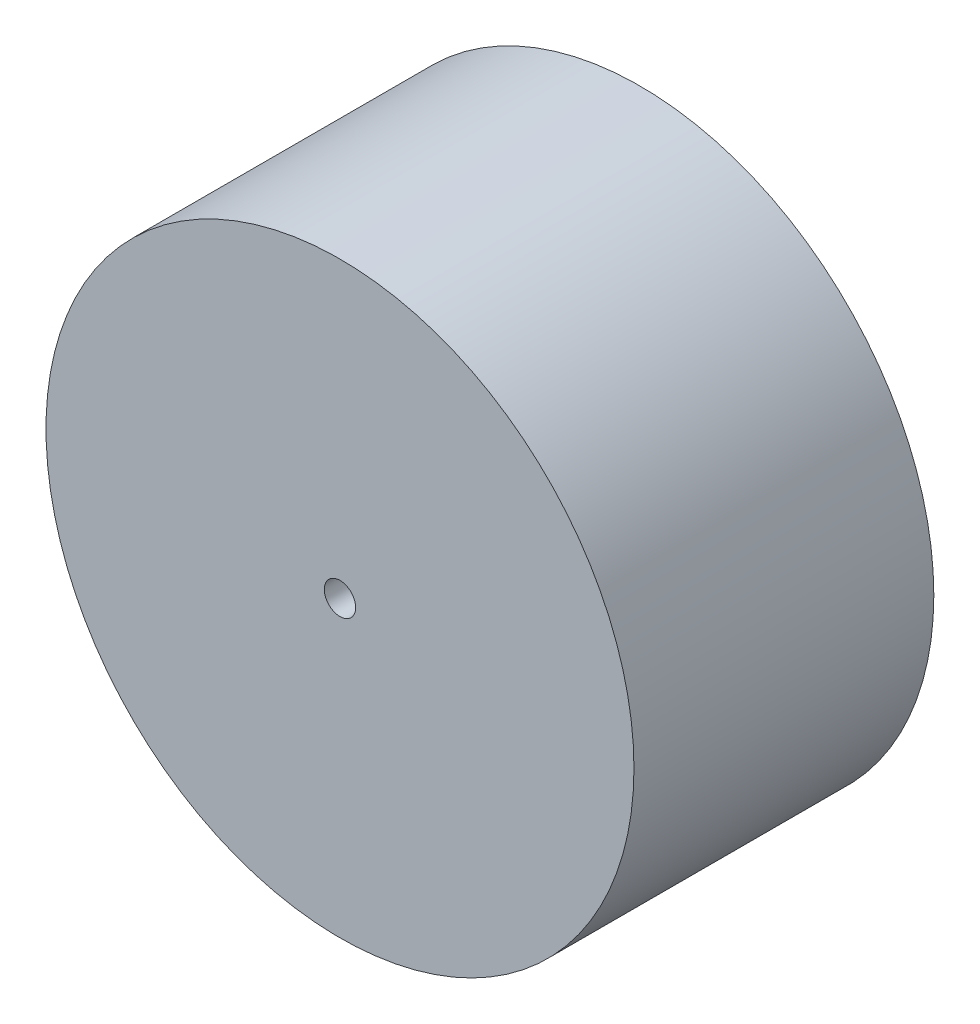
SolidWorks part; units mm, degrees
ref_plane "前视基准面" through (0, 0, 0) normal (0, 0, 1) x (1, 0, 0)
ref_plane "上视基准面" through (0, 0, 0) normal (0, 1, 0) x (1, 0, 0)
ref_plane "右视基准面" through (0, 0, 0) normal (1, 0, 0) x (0, 0, -1)
other "Configuration Table"
sketch "草图1" plane through (0, 0, 0) normal (0, 0, 1) x (1, 0, 0)
  circle A0 centre (0, 0) radius 30
  circle A1 centre (0, 0) radius 1.6
  dimension "D1" = 60
  dimension "D2" = 3.2
extrude "凸台-拉伸1" add sketch "草图1" along normal blind 30.6
